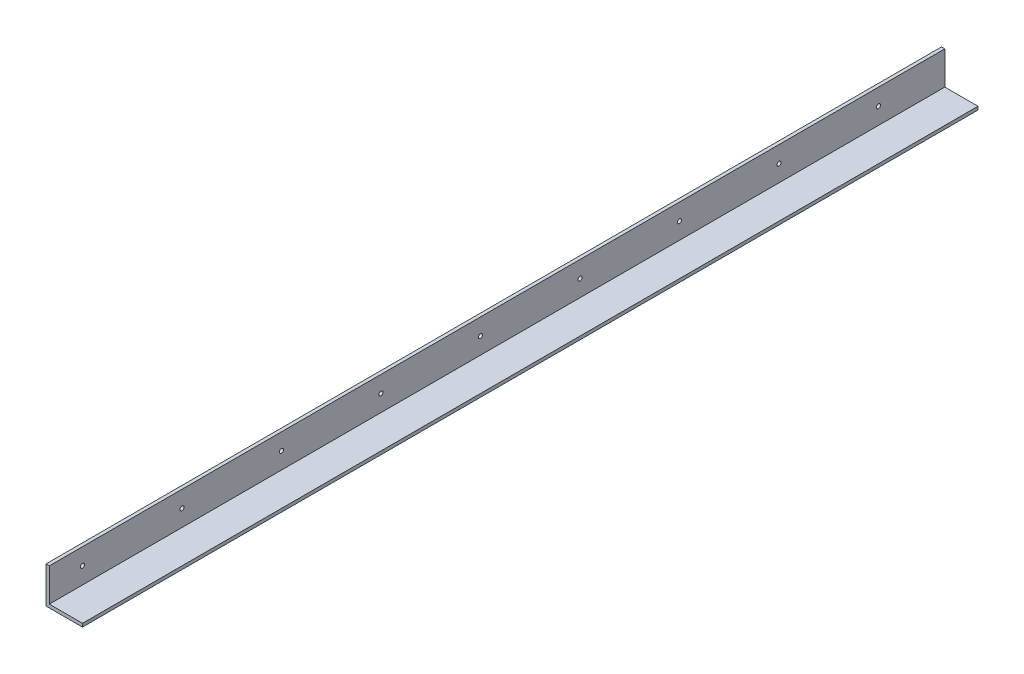
SolidWorks part; units mm, degrees
ref_plane "Front Plane" through (0, 0, 0) normal (0, 0, 1) x (1, 0, 0)
ref_plane "Top Plane" through (0, 0, 0) normal (0, 1, 0) x (1, 0, 0)
ref_plane "Right Plane" through (0, 0, 0) normal (1, 0, 0) x (0, 0, -1)
ref_plane "Plane1" through (0, 0, -50) normal (0, 0, -1) x (-1, 0, 0)
sketch "Sketch1" plane through (0, 0, -50) normal (0, 0, -1) x (-1, 0, 0)
  line L0 (0, 44) -> (-4, 44)
  line L1 (-4, 44) -> (-4, 4)
  line L2 (-4, 4) -> (-44, 4)
  line L3 (-44, 4) -> (-44, 0)
  line L4 (-44, 0) -> (0, 0)
  line L5 (0, 0) -> (0, 44)
  dimension "D1" = 4
  dimension "D2" = 4
  dimension "D3" = 40
  dimension "D4" = 40
extrude "Boss-Extrude1" add sketch "Sketch1" against normal blind 1080
sketch "Sketch2" plane through (4, 0, 0) normal (1, 0, 0) x (0, 0, -1)
  line L0 (-1030, 44) -> (-1030, 4) construction
  line L1 (-1030, 44) -> (50, 44) construction
  line L2 (-1030, 4) -> (50, 4) construction
  line L3 (-1030, 4) -> (50, 4) construction
  line L4 (-1030, 44) -> (50, 44) construction
  line L5 (-1033.9843, 44) -> (-1033.9843, 4) construction
  line L6 (-1033.9843, 24) -> (-990, 24) construction
  circle A0 centre (-990, 24) radius 2.5
  circle A1 centre (-870, 24) radius 2.5
  circle A2 centre (-750, 24) radius 2.5
  circle A3 centre (-630, 24) radius 2.5
  circle A4 centre (-510, 24) radius 2.5
  circle A5 centre (-390, 24) radius 2.5
  circle A6 centre (-270, 24) radius 2.5
  circle A7 centre (-150, 24) radius 2.5
  circle A8 centre (-30, 24) radius 2.5
  dimension "D1" = 40
  dimension "D2" = 5
  dimension "D3" = 9
extrude "Cut-Extrude1" cut sketch "Sketch2" against normal through all
